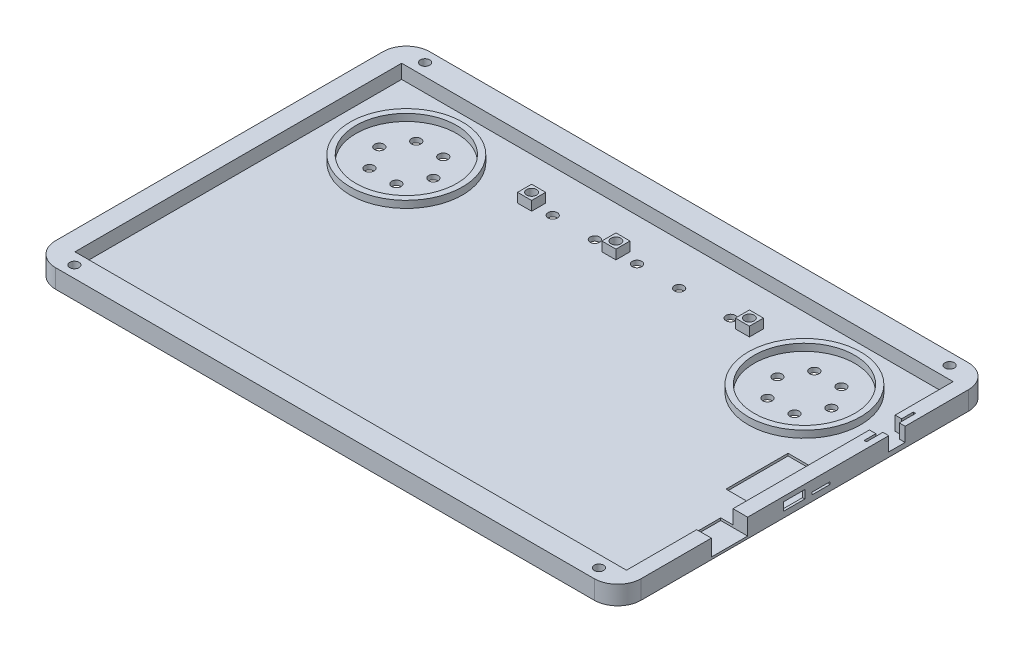
SolidWorks part; units mm, degrees
ref_plane "前视基准面" through (0, 0, 0) normal (0, 0, 1) x (1, 0, 0)
ref_plane "上视基准面" through (0, 0, 0) normal (0, 1, 0) x (1, 0, 0)
ref_plane "右视基准面" through (0, 0, 0) normal (1, 0, 0) x (0, 0, -1)
sketch "草图1" plane through (0, 0, 0) normal (0, 1, 0) x (1, 0, 0)
  line L1 (-106.707, 68.7882) -> (123.293, 68.7882)
  line L2 (-116.707, 58.7882) -> (-116.707, -80.9618)
  line L3 (-106.707, -90.9618) -> (123.293, -90.9618)
  line L4 (133.293, 58.7882) -> (133.293, -80.9618)
  arc A0 (123.293, 68.7882) -> (133.293, 58.7882) centre (123.293, 58.7882) cw
  arc A1 (123.293, -90.9618) -> (133.293, -80.9618) centre (123.293, -80.9618) ccw
  arc A2 (-106.707, -90.9618) -> (-116.707, -80.9618) centre (-106.707, -80.9618) cw
  arc A3 (-116.707, 58.7882) -> (-106.707, 68.7882) centre (-106.707, 58.7882) cw
  point P6 (133.293, 68.7882)
  point P9 (133.293, -90.9618)
  point P14 (-116.707, 68.7882)
  dimension "D3" = 10
  dimension "D1" = 159.75
  dimension "D2" = 250
extrude "凸台-拉伸1" add sketch "草图1" along normal blind 8
sketch "草图2" plane through (0, 8, 0) normal (0, 1, 0) x (1, 0, 0)
  line L0 (-116.707, 58.7882) -> (-116.707, -80.9618) construction
  line L1 (-103.707, 63.7882) -> (120.293, 63.7882) construction
  line L2 (-103.707, 63.7882) -> (-103.707, -85.9618) construction
  line L3 (-103.707, -85.9618) -> (120.293, -85.9618) construction
  line L4 (120.293, 63.7882) -> (120.293, -85.9618) construction
  line L5 (133.293, -80.9618) -> (133.293, 58.7882) construction
  line L6 (123.293, 68.7882) -> (-106.707, 68.7882) construction
  line L7 (-106.707, -90.9618) -> (123.293, -90.9618) construction
  circle A0 centre (-103.707, 63.7882) radius 2
  circle A1 centre (-103.707, -85.9618) radius 2
  circle A2 centre (120.293, -85.9618) radius 2
  circle A3 centre (120.293, 63.7882) radius 2
  dimension "D1" = 13
  dimension "D2" = 13
  dimension "D3" = 5
  dimension "D4" = 5
extrude "切除-拉伸1" cut sketch "草图2" against normal blind 8
sketch "草图3" plane through (0, 8, 0) normal (0, 1, 0) x (1, 0, 0)
  line L0 (-116.707, 58.7882) -> (-116.707, -80.9618) construction
  line L1 (-108.457, 58.5382) -> (127.043, 58.5382)
  line L2 (-108.457, 58.5382) -> (-108.457, -80.9618)
  line L3 (-108.457, -80.9618) -> (127.043, -80.9618)
  line L4 (127.043, 58.5382) -> (127.043, -80.9618)
  line L5 (123.293, 68.7882) -> (-106.707, 68.7882) construction
  line L6 (133.293, -80.9618) -> (133.293, 58.7882) construction
  line L7 (-106.707, -90.9618) -> (123.293, -90.9618) construction
  dimension "D1" = 8.25
  dimension "D2" = 10.25
  dimension "D3" = 235.5
  dimension "D4" = 139.5
  dimension "D5" = 6.25
  dimension "D6" = 10
extrude "切除-拉伸2" cut sketch "草图3" against normal blind 6
sketch "草图4" plane through (0, 2, 0) normal (0, 1, 0) x (1, 0, 0)
  line L0 (123.293, 68.7882) -> (-106.707, 68.7882) construction
  line L1 (-45.457, 50.5382) -> (62.043, 50.5382) construction
  line L2 (-45.457, 50.5382) -> (-45.457, 35.5382) construction
  line L3 (-45.457, 35.5382) -> (62.043, 35.5382) construction
  line L4 (62.043, 50.5382) -> (62.043, 35.5382) construction
  line L5 (127.043, 58.5382) -> (-108.457, 58.5382) construction
  line L6 (-45.457, 40.5382) -> (62.043, 40.5382) construction
  line L7 (-33.0886, 43.5382) -> (60.5097, 43.5382) construction
  line L8 (53.043, 37.5382) -> (47.043, 37.5382) construction
  line L9 (53.043, 37.5382) -> (53.043, 43.5382) construction
  line L10 (53.043, 43.5382) -> (47.043, 43.5382) construction
  line L11 (47.043, 37.5382) -> (47.043, 43.5382) construction
  line L12 (53.043, 37.5382) -> (47.043, 43.5382) construction
  line L13 (53.043, 43.5382) -> (47.043, 37.5382) construction
  line L14 (31.043, 37.5382) -> (25.043, 37.5382) construction
  line L15 (31.043, 37.5382) -> (31.043, 43.5382) construction
  line L16 (31.043, 43.5382) -> (25.043, 43.5382) construction
  line L17 (25.043, 37.5382) -> (25.043, 43.5382) construction
  line L18 (31.043, 37.5382) -> (25.043, 43.5382) construction
  line L19 (31.043, 43.5382) -> (25.043, 37.5382) construction
  line L20 (13.043, 37.5382) -> (7.043, 37.5382) construction
  line L21 (13.043, 37.5382) -> (13.043, 43.5382) construction
  line L22 (13.043, 43.5382) -> (7.043, 43.5382) construction
  line L23 (7.043, 37.5382) -> (7.043, 43.5382) construction
  line L24 (13.043, 37.5382) -> (7.043, 43.5382) construction
  line L25 (13.043, 43.5382) -> (7.043, 37.5382) construction
  line L26 (-4.957, 37.5382) -> (-10.957, 37.5382) construction
  line L27 (-4.957, 37.5382) -> (-4.957, 43.5382) construction
  line L28 (-4.957, 43.5382) -> (-10.957, 43.5382) construction
  line L29 (-10.957, 37.5382) -> (-10.957, 43.5382) construction
  line L30 (-4.957, 37.5382) -> (-10.957, 43.5382) construction
  line L31 (-4.957, 43.5382) -> (-10.957, 37.5382) construction
  line L32 (-22.957, 37.5382) -> (-28.957, 37.5382) construction
  line L33 (-22.957, 37.5382) -> (-22.957, 43.5382) construction
  line L34 (-22.957, 43.5382) -> (-28.957, 43.5382) construction
  line L35 (-28.957, 37.5382) -> (-28.957, 43.5382) construction
  line L36 (-22.957, 37.5382) -> (-28.957, 43.5382) construction
  line L37 (-22.957, 43.5382) -> (-28.957, 37.5382) construction
  line L38 (-33.0053, 37.5382) -> (60.5917, 37.5382) construction
  circle A0 centre (-25.957, 40.5382) radius 2
  circle A1 centre (-7.957, 40.5382) radius 2
  circle A2 centre (10.043, 40.5382) radius 2
  circle A3 centre (28.043, 40.5382) radius 2
  circle A4 centre (50.043, 40.5382) radius 2
  point P4 (8.293, 50.5382)
  point P5 (8.293, 68.7882)
  point P6 (50.043, 40.5382)
  point P17 (28.043, 40.5382)
  point P22 (10.043, 40.5382)
  point P27 (-7.957, 40.5382)
  point P32 (-25.957, 40.5382)
  dimension "D1" = 107.5
  dimension "D2" = 15
  dimension "D3" = 8
  dimension "D4" = 5
  dimension "D5" = 6
  dimension "D6" = 6
  dimension "D7" = 6
  dimension "D8" = 6
  dimension "D9" = 6
  dimension "D10" = 6
  dimension "D11" = 9
  dimension "D12" = 16
  dimension "D13" = 12
  dimension "D14" = 12
  dimension "D15" = 12
extrude "切除-拉伸3" cut sketch "草图4" against normal blind 6
sketch "草图6" plane through (0, 2, 0) normal (0, 1, 0) x (1, 0, 0)
  line L0 (-45.457, 50.5382) -> (62.043, 50.5382) construction
  line L1 (-45.457, 50.5382) -> (-45.457, 35.5382) construction
  line L2 (-45.457, 35.5382) -> (62.043, 35.5382) construction
  line L3 (62.043, 50.5382) -> (62.043, 35.5382) construction
  line L4 (-45.457, 40.5382) -> (62.043, 40.5382) construction
  line L5 (-48.4126, 43.5382) -> (45.1857, 43.5382) construction
  line L6 (53.043, 37.5382) -> (47.043, 37.5382) construction
  line L7 (53.043, 37.5382) -> (53.043, 43.5382) construction
  line L8 (53.043, 43.5382) -> (47.043, 43.5382) construction
  line L9 (47.043, 37.5382) -> (47.043, 43.5382) construction
  line L10 (53.043, 37.5382) -> (47.043, 43.5382) construction
  line L11 (53.043, 43.5382) -> (47.043, 37.5382) construction
  line L12 (31.043, 37.5382) -> (25.043, 37.5382) construction
  line L13 (31.043, 37.5382) -> (31.043, 43.5382) construction
  line L14 (31.043, 43.5382) -> (25.043, 43.5382) construction
  line L15 (25.043, 37.5382) -> (25.043, 43.5382) construction
  line L16 (31.043, 37.5382) -> (25.043, 43.5382) construction
  line L17 (31.043, 43.5382) -> (25.043, 37.5382) construction
  line L18 (13.043, 37.5382) -> (7.043, 37.5382) construction
  line L19 (13.043, 37.5382) -> (13.043, 43.5382) construction
  line L20 (13.043, 43.5382) -> (7.043, 43.5382) construction
  line L21 (7.043, 37.5382) -> (7.043, 43.5382) construction
  line L22 (13.043, 37.5382) -> (7.043, 43.5382) construction
  line L23 (13.043, 43.5382) -> (7.043, 37.5382) construction
  line L24 (-4.957, 37.5382) -> (-10.957, 37.5382) construction
  line L25 (-4.957, 37.5382) -> (-4.957, 43.5382) construction
  line L26 (-4.957, 43.5382) -> (-10.957, 43.5382) construction
  line L27 (-10.957, 37.5382) -> (-10.957, 43.5382) construction
  line L28 (-4.957, 37.5382) -> (-10.957, 43.5382) construction
  line L29 (-4.957, 43.5382) -> (-10.957, 37.5382) construction
  line L30 (-22.957, 37.5382) -> (-28.957, 37.5382) construction
  line L31 (-22.957, 37.5382) -> (-22.957, 43.5382) construction
  line L32 (-22.957, 43.5382) -> (-28.957, 43.5382) construction
  line L33 (-28.957, 37.5382) -> (-28.957, 43.5382) construction
  line L34 (-22.957, 37.5382) -> (-28.957, 43.5382) construction
  line L35 (-22.957, 43.5382) -> (-28.957, 37.5382) construction
  line L36 (-48.3293, 37.5382) -> (45.2677, 37.5382) construction
  line L37 (123.293, 68.7882) -> (-106.707, 68.7882) construction
  line L38 (127.043, 58.5382) -> (-108.457, 58.5382) construction
  line L40 (61.043, 37.5382) -> (55.043, 37.5382)
  line L41 (61.043, 37.5382) -> (61.043, 43.5382)
  line L42 (61.043, 43.5382) -> (55.043, 43.5382)
  line L43 (55.043, 37.5382) -> (55.043, 43.5382)
  line L44 (61.043, 37.5382) -> (55.043, 43.5382) construction
  line L45 (61.043, 43.5382) -> (55.043, 37.5382) construction
  line L46 (4.043, 37.5382) -> (-1.957, 37.5382)
  line L47 (4.043, 37.5382) -> (4.043, 43.5382)
  line L48 (4.043, 43.5382) -> (-1.957, 43.5382)
  line L49 (-1.957, 37.5382) -> (-1.957, 43.5382)
  line L50 (4.043, 37.5382) -> (-1.957, 43.5382) construction
  line L51 (4.043, 43.5382) -> (-1.957, 37.5382) construction
  line L52 (-31.957, 37.5382) -> (-37.957, 37.5382)
  line L53 (-31.957, 37.5382) -> (-31.957, 43.5382)
  line L54 (-31.957, 43.5382) -> (-37.957, 43.5382)
  line L55 (-37.957, 37.5382) -> (-37.957, 43.5382)
  line L56 (-31.957, 37.5382) -> (-37.957, 43.5382) construction
  line L57 (-31.957, 43.5382) -> (-37.957, 37.5382) construction
  circle A6 centre (-34.957, 40.5382) radius 2.1
  circle A7 centre (1.043, 40.5382) radius 2.1
  circle A8 centre (58.043, 40.5382) radius 2.1
  point P4 (8.293, 50.5382)
  point P5 (50.043, 40.5382)
  point P12 (28.043, 40.5382)
  point P17 (10.043, 40.5382)
  point P22 (-7.957, 40.5382)
  point P27 (-25.957, 40.5382)
  point P35 (58.043, 40.5382)
  point P41 (1.043, 40.5382)
  point P46 (8.293, 68.7882)
  point P47 (-34.957, 40.5382)
  dimension "D1" = 107.5
  dimension "D2" = 15
  dimension "D3" = 5
  dimension "D4" = 6
  dimension "D5" = 6
  dimension "D6" = 6
  dimension "D7" = 6
  dimension "D8" = 6
  dimension "D9" = 6
  dimension "D10" = 9
  dimension "D11" = 16
  dimension "D12" = 12
  dimension "D13" = 12
  dimension "D14" = 12
  dimension "D15" = 8
  dimension "D16" = 6
  dimension "D17" = 5
  dimension "D18" = 9
  dimension "D19" = 6
  dimension "D20" = 6
  dimension "D21" = 6
extrude "凸台-拉伸2" add sketch "草图6" along normal blind 4
sketch "草图7" plane through (0, 2, 0) normal (0, 1, 0) x (1, 0, 0)
  line L0 (123.293, 68.7882) -> (-106.707, 68.7882) construction
  line L3 (-116.707, 58.7882) -> (-116.707, -80.9618) construction
  line L4 (133.293, -80.9618) -> (133.293, 58.7882) construction
  circle A0 centre (-76.707, 28.7882) radius 21.5
  circle A1 centre (93.293, 28.7882) radius 21.5
  circle A2 centre (-76.707, 28.7882) radius 24
  circle A3 centre (93.293, 28.7882) radius 24
  dimension "D1" = 40
  dimension "D2" = 40
  dimension "D3" = 40
  dimension "D4" = 40
extrude "凸台-拉伸3" add sketch "草图7" along normal blind 3
sketch "草图8" plane through (0, 2, 0) normal (0, 1, 0) x (1, 0, 0)
  line L1 (-82.4805, 38.7882) -> (-88.254, 28.7882) construction
  line L2 (-88.254, 28.7882) -> (-82.4805, 18.7882) construction
  line L3 (-82.4805, 18.7882) -> (-70.9335, 18.7882) construction
  line L4 (-70.9335, 18.7882) -> (-65.16, 28.7882) construction
  line L5 (-65.16, 28.7882) -> (-70.9335, 38.7882) construction
  line L6 (-70.9335, 38.7882) -> (-82.4805, 38.7882) construction
  line L7 (87.5195, 38.7882) -> (81.746, 28.7882) construction
  line L8 (81.746, 28.7882) -> (87.5195, 18.7882) construction
  line L9 (87.5195, 18.7882) -> (99.0665, 18.7882) construction
  line L10 (99.0665, 18.7882) -> (104.84, 28.7882) construction
  line L11 (104.84, 28.7882) -> (99.0665, 38.7882) construction
  line L12 (99.0665, 38.7882) -> (87.5195, 38.7882) construction
  circle A0 centre (-76.707, 28.7882) radius 10 construction
  circle A1 centre (93.293, 28.7882) radius 10 construction
  circle A2 centre (-82.4805, 38.7882) radius 2
  circle A3 centre (-70.9335, 38.7882) radius 2
  circle A4 centre (-65.16, 28.7882) radius 2
  circle A5 centre (-70.9335, 18.7882) radius 2
  circle A6 centre (-82.4805, 18.7882) radius 2
  circle A7 centre (-88.254, 28.7882) radius 2
  circle A8 centre (87.5195, 38.7882) radius 2
  circle A9 centre (99.0665, 38.7882) radius 2
  circle A10 centre (104.84, 28.7882) radius 2
  circle A11 centre (99.0665, 18.7882) radius 2
  circle A12 centre (87.5195, 18.7882) radius 2
  circle A13 centre (81.746, 28.7882) radius 2
  point P0 (-76.707, 28.7882)
  point P1 (93.293, 28.7882)
extrude "切除-拉伸4" cut sketch "草图8" against normal blind 3
sketch "草图9" plane through (0, 8, 0) normal (0, 1, 0) x (1, 0, 0)
  line L0 (133.293, -80.9618) -> (133.293, 58.7882) construction
  line L1 (133.293, -35.4618) -> (121.793, -35.4618)
  line L2 (133.293, -35.4618) -> (133.293, -50.9618)
  line L3 (133.293, -50.9618) -> (121.793, -50.9618)
  line L4 (121.793, -35.4618) -> (121.793, -50.9618)
  line L6 (-106.707, -90.9618) -> (123.293, -90.9618) construction
  dimension "D1" = 15.5
  dimension "D2" = 11.5
  dimension "D3" = 55.5
extrude "切除-拉伸5" cut sketch "草图9" against normal blind 7
sketch "草图10" plane through (0, 8, 0) normal (0, 1, 0) x (1, 0, 0)
  line L0 (127.043, -35.4618) -> (127.043, 58.5382) construction
  line L2 (127.043, 33.7882) -> (127.043, 22.7882)
  line L5 (133.293, -35.4618) -> (133.293, 58.7882) construction
  line L6 (129.793, 33.7882) -> (127.043, 33.7882)
  line L7 (130.793, 31.7882) -> (133.293, 31.7882)
  line L9 (130.793, 24.7882) -> (133.293, 24.7882)
  line L10 (133.293, 31.7882) -> (133.293, 24.7882)
  line L12 (130.793, 31.7882) -> (130.793, 38.7882)
  line L13 (130.793, 38.7882) -> (129.793, 38.7882)
  line L14 (129.793, 33.7882) -> (129.793, 38.7882)
  line L16 (130.793, 24.7882) -> (130.793, 17.7882)
  line L17 (130.793, 17.7882) -> (129.793, 17.7882)
  line L18 (129.793, 22.7882) -> (129.793, 17.7882)
  line L19 (127.043, 22.7882) -> (129.793, 22.7882)
  line L20 (123.293, 68.7882) -> (-106.707, 68.7882) construction
  point P12 (127.043, 28.2882)
  point P13 (133.293, 28.2882)
  dimension "D1" = 5
  dimension "D2" = 11
  dimension "D3" = 7
  dimension "D4" = 5
  dimension "D5" = 1
  dimension "D6" = 35
  dimension "D7" = 1
  dimension "D8" = 2.5
  dimension "D9" = 2.5
extrude "切除-拉伸6" cut sketch "草图10" against normal blind 6
sketch "草图11" plane through (0, 2, 0) normal (0, 1, 0) x (1, 0, 0)
  line L7 (133.293, -35.4618) -> (133.293, 24.7882) construction
  line L8 (112.293, 2.7882) -> (132.293, 2.7882)
  line L9 (112.293, 2.7882) -> (112.293, -23.7118)
  line L10 (112.293, -23.7118) -> (132.293, -23.7118)
  line L11 (132.293, 2.7882) -> (132.293, -23.7118)
  line L12 (127.043, 22.7882) -> (129.793, 22.7882) construction
  dimension "D1" = 26.5
  dimension "D2" = 20
  dimension "D3" = 1
  dimension "D4" = 20
extrude "切除-拉伸8" cut sketch "草图11" against normal blind 1
sketch "草图13" plane through (127.043, 0, 0) normal (-1, 0, 0) x (0, 0, 1)
  line L1 (-2.7882, 2) -> (23.7118, 2)
  line L2 (-2.7882, 2) -> (-2.7882, 7.5)
  line L3 (-2.7882, 7.5) -> (23.7118, 7.5)
  line L4 (23.7118, 2) -> (23.7118, 7.5)
  dimension "D1" = 26.5
  dimension "D2" = 5.5
extrude "切除-拉伸9" cut sketch "草图13" against normal blind 5.25
sketch "草图14" plane through (132.293, 0, 0) normal (-1, 0, 0) x (0, 0, 1)
  line L0 (23.7118, 1) -> (-2.7882, 1) construction
  line L1 (20.2118, 2.5) -> (11.0118, 2.5)
  line L2 (20.2118, 2.5) -> (20.2118, 6)
  line L3 (20.2118, 6) -> (11.0118, 6)
  line L4 (11.0118, 2.5) -> (11.0118, 6)
  line L5 (23.7118, 1) -> (23.7118, 7.5) construction
  line L6 (-2.7882, 1) -> (-2.7882, 7.5) construction
  line L7 (8.0118, 2.5) -> (0.2118, 2.5)
  line L8 (8.0118, 2.5) -> (8.0118, 3.5)
  line L9 (8.0118, 3.5) -> (0.2118, 3.5)
  line L10 (0.2118, 2.5) -> (0.2118, 3.5)
  dimension "D1" = 1.5
  dimension "D2" = 3.5
  dimension "D3" = 9.2
  dimension "D4" = 1.5
  dimension "D5" = 3
  dimension "D6" = 3
  dimension "D7" = 1
  dimension "D8" = 3.5
extrude "切除-拉伸10" cut sketch "草图14" against normal blind 5.25
sketch "草图15" plane through (127.043, 0, 0) normal (-1, 0, 0) x (0, 0, 1)
  line L0 (-2.7882, 7.5) -> (-0.2882, 7.5)
  line L1 (23.7118, 7.5) -> (-2.7882, 7.5) construction
  line L2 (-0.2882, 7.5) -> (-2.7882, 5)
  line L3 (-2.7882, 7.5) -> (-2.7882, 2) construction
  line L4 (-2.7882, 5) -> (-2.7882, 7.5)
  dimension "D1" = 2.5
  dimension "D2" = 2.5
extrude "凸台-拉伸5" add sketch "草图15" against normal blind 5.25
sketch "草图16" plane through (127.043, 0, 0) normal (-1, 0, 0) x (0, 0, 1)
  line L0 (23.7118, 7.5) -> (23.7118, 5.5)
  line L1 (23.7118, 2) -> (23.7118, 7.5) construction
  line L2 (23.7118, 5.5) -> (21.7118, 7.5)
  line L3 (23.7118, 7.5) -> (-0.2882, 7.5) construction
  line L4 (21.7118, 7.5) -> (23.7118, 7.5)
  dimension "D1" = 2
  dimension "D2" = 2
extrude "凸台-拉伸6" add sketch "草图16" against normal blind 5.25
sketch "草图17" plane through (0, 0, 0) normal (0, -1, 0) x (1, 0, 0)
  circle A0 centre (-103.707, 85.9618) radius 3
  circle A1 centre (120.293, 85.9618) radius 3
  circle A2 centre (120.293, -63.7882) radius 3
  circle A3 centre (-103.707, -63.7882) radius 3
extrude "切除-拉伸11" cut sketch "草图17" against normal blind 2
